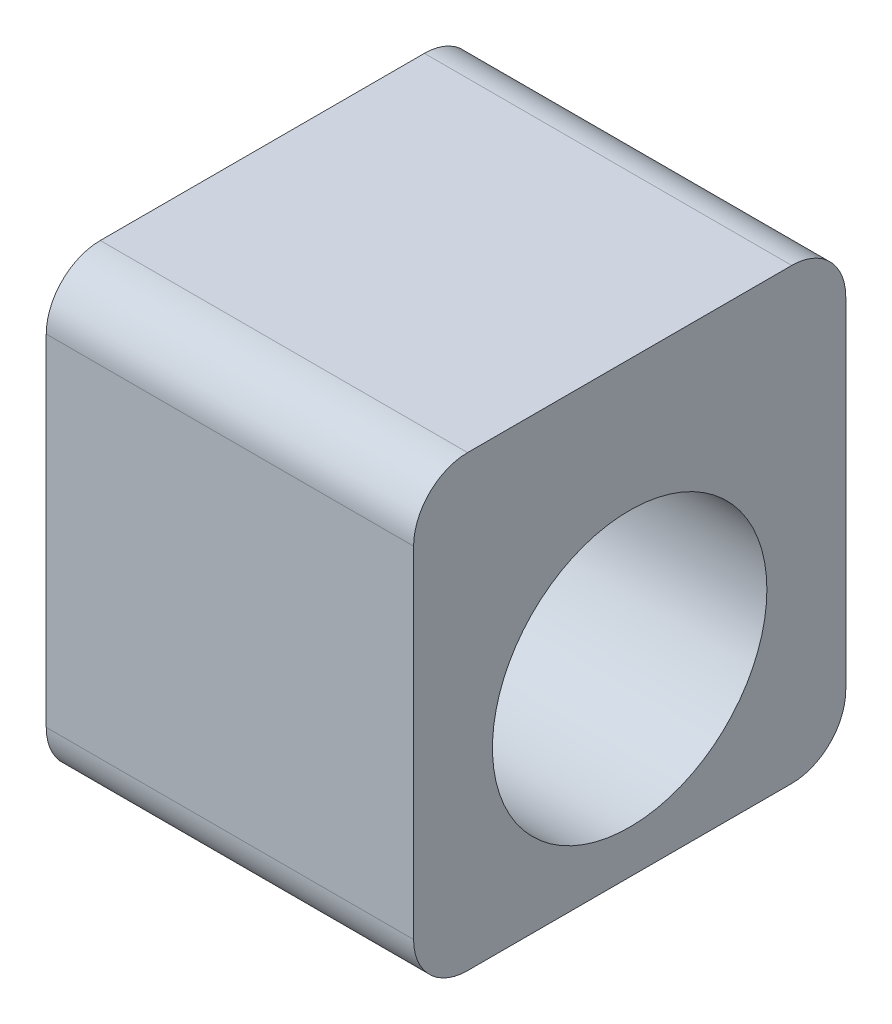
SolidWorks part; units mm, degrees
ref_plane "Front Plane" through (0, 0, 0) normal (0, 0, 1) x (1, 0, 0)
ref_plane "Top Plane" through (0, 0, 0) normal (0, 1, 0) x (1, 0, 0)
ref_plane "Right Plane" through (0, 0, 0) normal (1, 0, 0) x (0, 0, -1)
sketch "Sketch1" plane through (0, 0, 0) normal (1, 0, 0) x (0, 0, -1)
  line L0 (-15, -16.7) -> (15, -16.7)
  line L1 (20, -11.7) -> (20, 19.826)
  line L2 (15, 24.826) -> (-15, 24.826)
  line L3 (-20, 19.826) -> (-20, -11.7)
  arc A0 (15, -16.7) -> (20, -11.7) centre (15, -11.7) ccw
  arc A1 (20, 19.826) -> (15, 24.826) centre (15, 19.826) ccw
  arc A2 (-15, 24.826) -> (-20, 19.826) centre (-15, 19.826) ccw
  arc A3 (-20, -11.7) -> (-15, -16.7) centre (-15, -11.7) ccw
  circle A4 centre (0, 0) radius 12.7
extrude "Boss-Extrude1" add sketch "Sketch1" along normal mid plane 34
